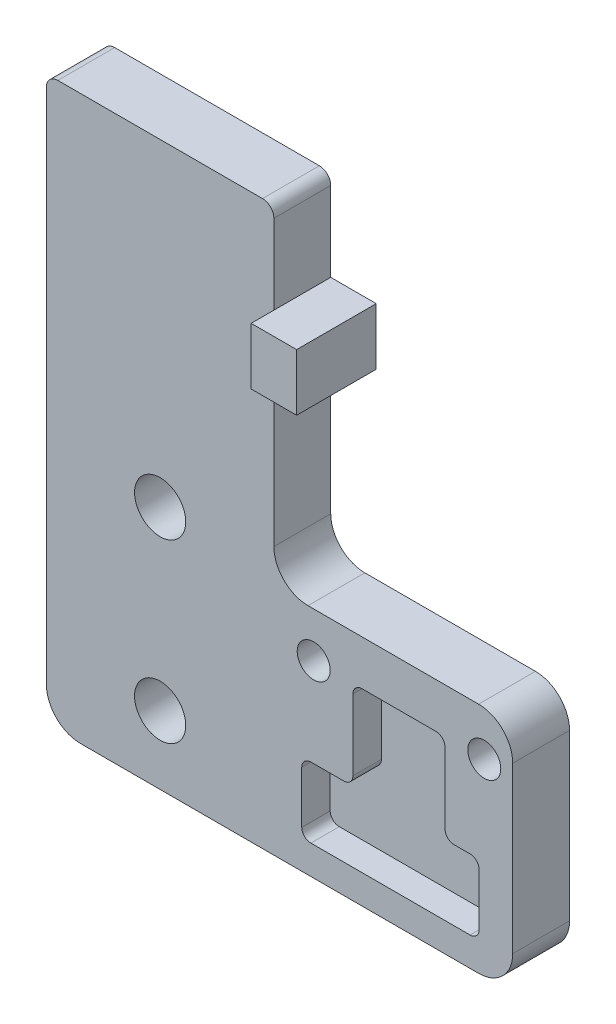
SolidWorks part; units mm, degrees
ref_plane "Alzado" through (0, 0, 0) normal (0, 0, 1) x (1, 0, 0)
ref_plane "Planta" through (0, 0, 0) normal (0, 1, 0) x (1, 0, 0)
ref_plane "Vista lateral" through (0, 0, 0) normal (1, 0, 0) x (0, 0, -1)
ref_plane "Plano1" through (0, 0, 5) normal (0, 0, 1) x (1, 0, 0)
sketch "Croquis1" plane through (0, 0, 5) normal (0, 0, 1) x (1, 0, 0)
  line L0 (20.5, -10.5) -> (20.5, 39)
  line L1 (20.5, 39) -> (-20.5, 39)
  line L2 (-20.5, 39) -> (-20.5, -10.5)
  line L3 (-20.5, -10.5) -> (20.5, -10.5)
extrude "Saliente-Extruir1" add sketch "Croquis1" against normal blind 5
sketch "Croquis2" plane through (0, 0, 5) normal (0, 0, 1) x (1, 0, 0)
  line L0 (-0.5, 39) -> (-0.5, 10)
  line L1 (-0.5, 10) -> (20.5, 10)
  line L2 (20.5, 10) -> (20.5, 39)
  line L3 (20.5, 39) -> (-0.5, 39)
extrude "Cortar-Extruir1" cut sketch "Croquis2" against normal through all
sketch "Croquis3" plane through (-0.5, 0, 0) normal (1, 0, 0) x (0, 0, -1)
  line L0 (0, 39) -> (0, 26)
  line L1 (0, 26) -> (-5, 26)
  line L2 (-5, 26) -> (-5, 39)
  line L3 (-5, 39) -> (0, 39)
extrude "Saliente-Extruir2" add sketch "Croquis3" along normal blind 4
sketch "Croquis4" plane through (0, 0, 0) normal (0, 0, -1) x (-1, 0, 0)
  line L0 (-3.5, 31) -> (0.5, 31)
  line L1 (0.5, 31) -> (0.5, 39)
  line L2 (0.5, 39) -> (-3.5, 39)
  line L3 (-3.5, 39) -> (-3.5, 31)
extrude "Cortar-Extruir2" cut sketch "Croquis4" against normal through all
sketch "Croquis5" plane through (0, 0, 5) normal (0, 0, 1) x (1, 0, 0)
  line L0 (3.5, 31) -> (3.5, 26)
  line L1 (3.5, 26) -> (-0.5, 26)
  line L2 (-0.5, 26) -> (-0.5, 31)
  line L3 (-0.5, 31) -> (3.5, 31)
extrude "Saliente-Extruir3" add sketch "Croquis5" along normal blind 2
sketch "Croquis6" plane through (0, 0, 5) normal (0, 0, 1) x (1, 0, 0)
  line L0 (17.55, -1.78) -> (14.55, -1.78)
  line L1 (14.55, -1.78) -> (14.55, 6.05)
  line L2 (14.55, 6.05) -> (6.45, 6.05)
  line L3 (6.45, 6.05) -> (6.45, -1.78)
  line L4 (6.45, -1.78) -> (1.95, -1.78)
  line L5 (1.95, -1.78) -> (1.95, -7.9531)
  line L6 (1.95, -7.9531) -> (17.55, -7.9531)
  line L7 (17.55, -7.9531) -> (17.55, -1.78)
extrude "Cortar-Extruir3" cut sketch "Croquis6" against normal blind 2.5
hole_wizard "Diámetro de taladro Ø4.5 (4.5)1" positions "Croquis8" profile "Croquis7" hole size "Ø4.5" standard "Ansi Metric"
sketch "Croquis8" plane through (0, 0, 0) normal (0, 0, -1) x (-1, 0, 0)
  point P0 (10.5, 11)
  point P1 (10.5, -4.5)
sketch "Croquis7" plane through (-10.5, 11, 0) normal (1, 0, 0) x (0, 1, 0)
  line L0 (0, 0) -> (0, 7)
  line L1 (0, 7) -> (2.25, 7)
  line L2 (2.25, 7) -> (2.25, 0)
  line L5 (2.25, 0) -> (0, 0)
  line L11 (0, -6.35) -> (0, 107.95) construction
  dimension "Diámetro de taladro hasta el siguiente" = 4.5
  dimension "Profundidad de taladro hasta el siguiente" = 7
hole_wizard "Diámetro de taladro Ø2.9 (2.9)1" positions "Croquis10" profile "Croquis9" hole size "Ø2.9" standard "Ansi Metric"
sketch "Croquis10" plane through (0, 0, 0) normal (0, 0, -1) x (-1, 0, 0)
  point P0 (-3, 6.05)
  point P1 (-18, 6.05)
sketch "Croquis9" plane through (3, 6.05, 0) normal (1, 0, 0) x (0, 1, 0)
  line L0 (0, 0) -> (0, 7)
  line L1 (0, 7) -> (1.45, 7)
  line L2 (1.45, 7) -> (1.45, 0)
  line L5 (1.45, 0) -> (0, 0)
  line L11 (0, -6.35) -> (0, 107.95) construction
  dimension "Diámetro de taladro hasta el siguiente" = 2.9
  dimension "Profundidad de taladro hasta el siguiente" = 7
fillet "Redondeo1" radius 0.8 8 edges at (1.95, -7.9531, 3.75) (14.55, -1.78, 3.75) (17.55, -7.9531, 3.75) (17.55, -1.78, 3.75) (6.45, -1.78, 3.75) (1.95, -1.78, 3.75) (14.55, 6.05, 3.75) (6.45, 6.05, 3.75)
fillet "Redondeo2" radius 1 2 edges at (-20.5, 39, 2.5) (-0.5, 39, 2.5)
fillet "Redondeo3" radius 3 4 edges at (-0.5, 10, 2.5) (-20.5, -10.5, 2.5) (20.5, 10, 2.5) (20.5, -10.5, 2.5)
sketch "Croquis11" plane through (0, 0, 0) normal (0, 0, -1) x (-1, 0, 0)
  line L0 (10.5, -28.2394) -> (10.5, 57.6872) construction
sketch "Croquis12" plane through (0, 0, 5) normal (0, 0, 1) x (1, 0, 0)
  line L0 (-10.5, -28.2394) -> (-10.5, 57.6872) construction
